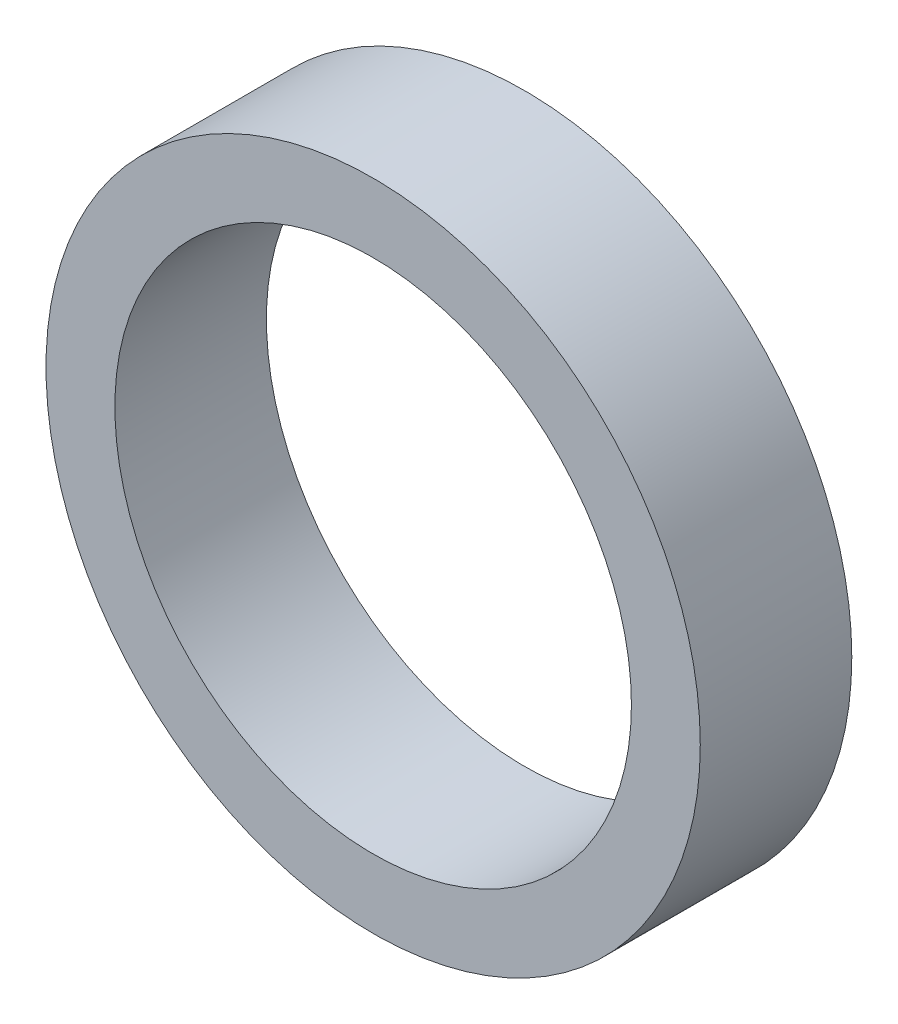
SolidWorks part; units mm, degrees
material "ABS"
ref_plane "Front Plane" through (0, 0, 0) normal (0, 0, 1) x (1, 0, 0)
ref_plane "Top Plane" through (0, 0, 0) normal (0, 1, 0) x (1, 0, 0)
ref_plane "Right Plane" through (0, 0, 0) normal (1, 0, 0) x (0, 0, -1)
sketch "Sketch1" plane through (0, 0, 0) normal (0, 0, 1) x (1, 0, 0)
  circle A0 centre (0, 0) radius 12.065
  circle A1 centre (0, 0) radius 9.525
  point P5 (0, -0.4861)
  dimension "D1" = 24.13
  dimension "D2" = 19.05
extrude "Boss-Extrude1" add sketch "Sketch1" along normal blind 5.588
